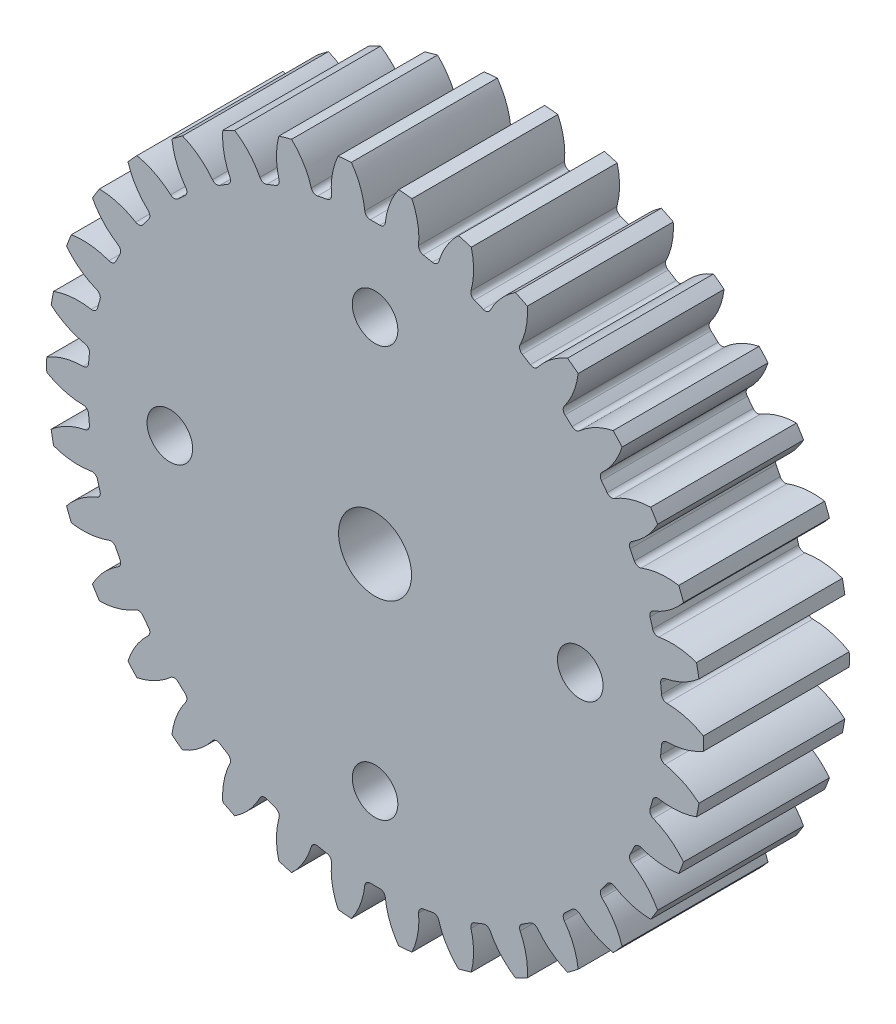
SolidWorks part; units mm, degrees
ref_plane "Ön Düzlem" through (0, 0, 0) normal (0, 0, 1) x (1, 0, 0)
ref_plane "Üst Düzlem" through (0, 0, 0) normal (0, 1, 0) x (1, 0, 0)
ref_plane "Sağ Düzlem" through (0, 0, 0) normal (1, 0, 0) x (0, 0, -1)
sketch "Çizim1" plane through (0, 0, 0) normal (0, 0, 1) x (1, 0, 0)
  circle A0 centre (0, 0) radius 34
  circle A1 centre (0, 0) radius 36
  circle A2 centre (0, 0) radius 31.5
  dimension "D1" = 68
  dimension "D2" = 72
  dimension "D3" = 63
extrude "Yükseklik-Ekstrüzyon1" add sketch "Çizim1" along normal mid plane 16 contours A1
sketch "Çizim2" plane through (0, 0, 8) normal (0, 0, 1) x (1, 0, 0)
  line L0 (0, 0) -> (0, 36) construction
  line L1 (-1.5702, 33.9637) -> (1.5702, 33.9637) construction
  line L2 (0, 29.6495) -> (-2.641, 36.9056) construction
  line L3 (0, 0) -> (-1.0881, 31.4812) construction
  line L4 (0, 0) -> (3.3217, 35.8464) construction
  line L5 (1.5702, 33.9637) -> (4.6973, 33.674) construction
  circle A0 centre (0, 0) radius 36 construction
  arc A1 (-3.3825, 36.8451) -> (-1.0881, 31.4812) centre (-9.1572, 31.2023) cw
  arc A2 (3.3825, 36.8451) -> (1.0881, 31.4812) centre (9.1572, 31.2023) ccw
  circle A3 centre (0, 0) radius 31.5 construction
  arc A4 (1.0881, 31.4812) -> (-1.0881, 31.4812) centre (0, 0) ccw
  circle A5 centre (0, 0) radius 34 construction
  circle A6 centre (0, 0) radius 36 construction
  circle A7 centre (0, 0) radius 37
  arc A8 (3.3825, 36.8451) -> (-3.3825, 36.8451) centre (0, 0) ccw
  dimension "D2" = 20
  dimension "D3" = 5.294
  dimension "D1" = 1
extrude "Kes-Ekstrüzyon1" cut sketch "Çizim2" against normal blind 16
fillet "Radyus1" radius 0.6 2 edges at (1.0881, 31.4812, 0) (-1.0881, 31.4812, 0)
pattern_circular "Dairesel Kaplama1" count 34 over 360 about axis through (0, 0, 0) along (0, 0, 1) of "Radyus1", "Kes-Ekstrüzyon1"
sketch "Sketch1" plane through (0, 0, 8) normal (0, 0, 1) x (1, 0, 0)
  circle A0 centre (0, 0) radius 4
  dimension "D1" = 8
extrude "Cut-Extrude1" cut sketch "Sketch1" against normal through all
sketch "Sketch2" plane through (0, 0, 8) normal (0, 0, 1) x (1, 0, 0)
  line L0 (-22.5, 0) -> (22.5, 0) construction
  line L1 (0, 22.5) -> (0, -22.5) construction
  circle A0 centre (0, 22.5) radius 2.5
  circle A1 centre (-22.5, 0) radius 2.5
  circle A2 centre (22.5, 0) radius 2.5
  circle A3 centre (0, -22.5) radius 2.5
  point P4 (0, 0)
  point P8 (0, 0)
  dimension "D3" = 5
  dimension "D4" = 5
  dimension "D5" = 5
  dimension "D6" = 5
  dimension "D1" = 45
  dimension "D2" = 45
extrude "Cut-Extrude2" cut sketch "Sketch2" against normal through all
equation "\"m\"= 2mm'modül"
equation "\"z\"= 34'diş sayısı"
equation "\"D1@Çizim1\"=\"m\"*\"z\""
equation "\"D2@Çizim1\"=\"m\"*(\"z\"+2)"
equation "\"D3@Çizim1\"=\"m\"*(\"z\"-2.5)"
equation "\"D1@Yükseklik-Ekstrüzyon1\"=\"m\"*8"
equation "\"D3@Çizim2\"=180/\"z\""
equation "\"D1\"= \"m\" * 8"
equation "\"D1@Radyus1\"=\"m\"*0.3"
equation "\"D1@Dairesel Kaplama1\"=\"z\""
equation "\"D1@Kes-Ekstrüzyon1\"=\"m\"*8"
